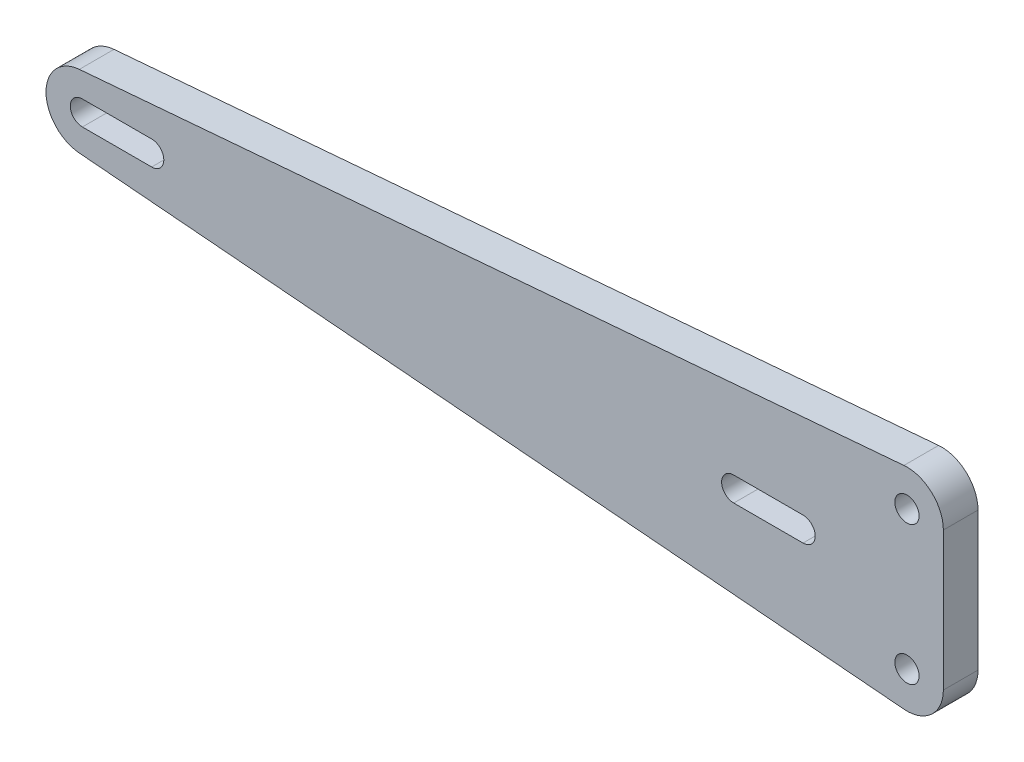
SolidWorks part; units mm, degrees
ref_plane "Plano frontal" through (0, 0, 0) normal (0, 0, 1) x (1, 0, 0)
ref_plane "Plano superior" through (0, 0, 0) normal (0, 1, 0) x (1, 0, 0)
ref_plane "Plano direito" through (0, 0, 0) normal (1, 0, 0) x (0, 0, -1)
sketch "Esboço1" plane through (0, 0, 0) normal (0, 0, 1) x (1, 0, 0)
  line L0 (-47, 0) -> (47, 0) construction
  line L1 (47, 0) -> (37, 0) construction
  line L2 (47, -1.75) -> (37, -1.75)
  line L3 (47, 1.75) -> (37, 1.75)
  line L4 (-47, 0) -> (-57, 0) construction
  line L5 (-47, -1.75) -> (-57, -1.75)
  line L6 (-47, 1.75) -> (-57, 1.75)
  line L7 (67.25, 10) -> (67.25, -10)
  line L8 (-57.4396, -5.2316) -> (61.5604, -15.2316)
  line L9 (-57.4396, 5.2316) -> (61.5604, 15.2316)
  arc A10 (47, -1.75) -> (47, 1.75) centre (47, 0) ccw
  arc A11 (37, 1.75) -> (37, -1.75) centre (37, 0) ccw
  arc A12 (-47, -1.75) -> (-47, 1.75) centre (-47, 0) ccw
  arc A13 (-57, 1.75) -> (-57, -1.75) centre (-57, 0) ccw
  circle A14 centre (62, -10) radius 1.75
  circle A15 centre (62, 10) radius 1.75
  arc A16 (61.5604, -15.2316) -> (67.25, -10) centre (62, -10) ccw
  arc A17 (67.25, 10) -> (61.5604, 15.2316) centre (62, 10) ccw
  arc A19 (-57.4396, 5.2316) -> (-57.4396, -5.2316) centre (-57, 0) ccw
  point P0 (0, 0)
  point P1 (42, 0)
  point P7 (-52, 0)
  dimension "D1" = 10
  dimension "D3" = 1.75
  dimension "D5" = 3.5
  dimension "D8" = 3.5
  dimension "D9" = 3.5
  dimension "D2" = 94
  dimension "D4" = 10
  dimension "D6" = 20
  dimension "D7" = 10
extrude "Ressalto-extrusão1" add sketch "Esboço1" along normal blind 5
